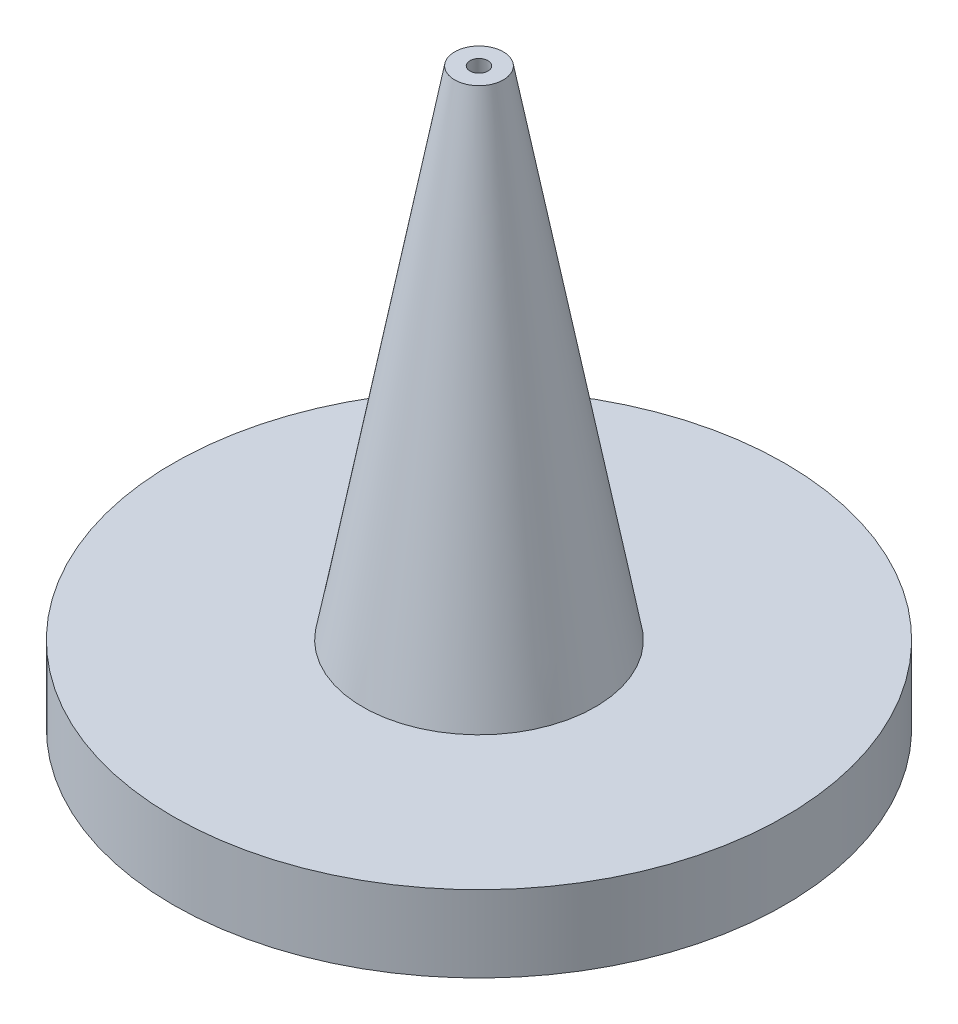
SolidWorks part; units mm, degrees
ref_plane "Front Plane" through (0, 0, 0) normal (0, 0, 1) x (1, 0, 0)
ref_plane "Top Plane" through (0, 0, 0) normal (0, 1, 0) x (1, 0, 0)
ref_plane "Right Plane" through (0, 0, 0) normal (1, 0, 0) x (0, 0, -1)
sketch "Sketch1" plane through (0, 0, 0) normal (0, 0, 1) x (1, 0, 0)
  line L0 (0, 0) -> (0, 19.05)
  line L1 (3.3528, 0) -> (10.16, 0)
  line L2 (0.2997, 19.05) -> (0.8077, 19.05)
  line L3 (10.16, 0) -> (10.16, 2.54)
  line L4 (0.8077, 19.05) -> (3.8608, 2.54)
  line L5 (3.3528, 0) -> (0.2997, 19.05)
  line L7 (10.16, 2.54) -> (3.8608, 2.54)
revolve "Revolve1" add sketch "Sketch1" angle 360 about L0
